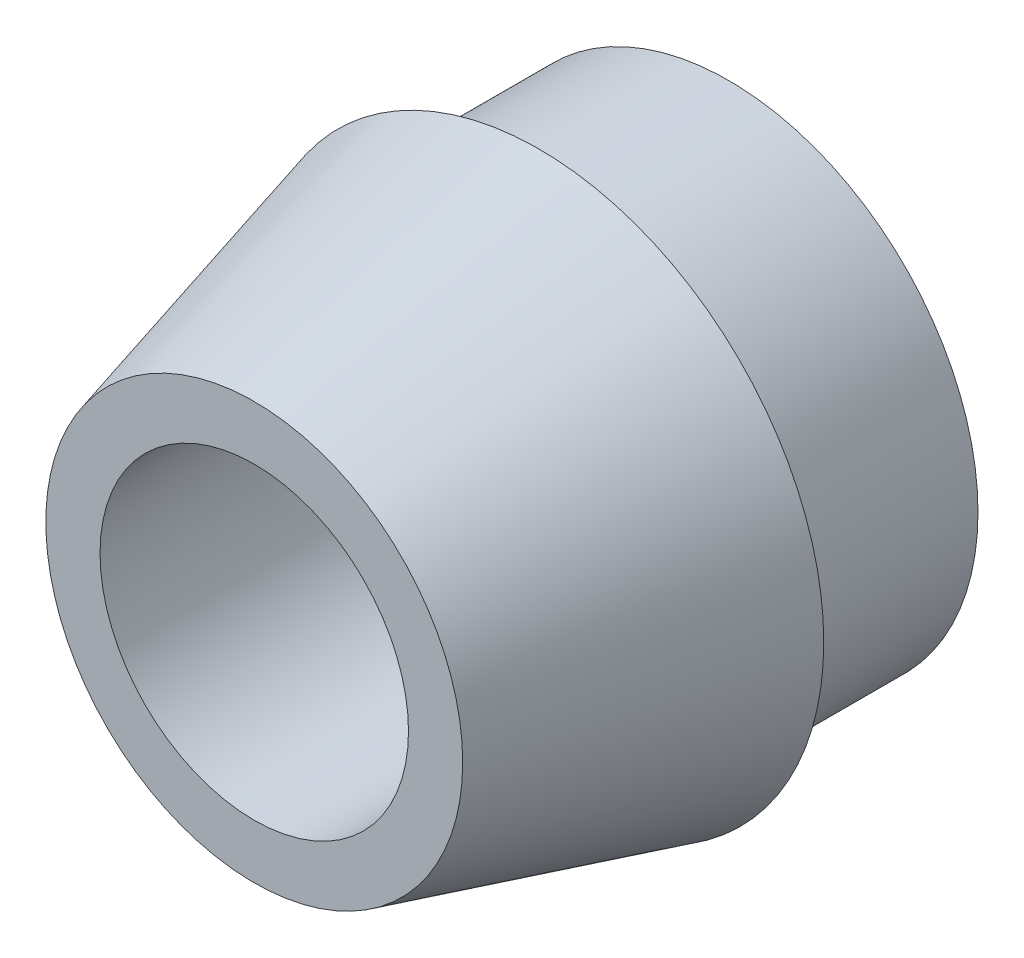
SolidWorks part; units mm, degrees
ref_plane "Front Plane" through (0, 0, 0) normal (0, 0, 1) x (1, 0, 0)
ref_plane "Top Plane" through (0, 0, 0) normal (0, 1, 0) x (1, 0, 0)
ref_plane "Right Plane" through (0, 0, 0) normal (1, 0, 0) x (0, 0, -1)
sketch "Sketch3" plane through (0, 0, 0) normal (0, 0, 1) x (1, 0, 0)
  circle A0 centre (0, 0) radius 52.5
  circle A1 centre (0, 0) radius 41.35
  dimension "D1" = 105
  dimension "D2" = 82.7
extrude "Boss-Extrude3" add sketch "Sketch3" along normal blind 40
sketch "Sketch6" plane through (0, 0, 40) normal (0, 0, 1) x (1, 0, 0)
  circle A0 centre (0, 0) radius 60
  dimension "D1" = 120
extrude "Boss-Extrude5" add sketch "Sketch6" along normal blind 60 draft 15
sketch "Sketch7" plane through (0, 0, 100) normal (0, 0, 1) x (1, 0, 0)
  circle A0 centre (0, 0) radius 32.5
  dimension "D1" = 65
extrude "Cut-Extrude1" cut sketch "Sketch7" against normal through all
